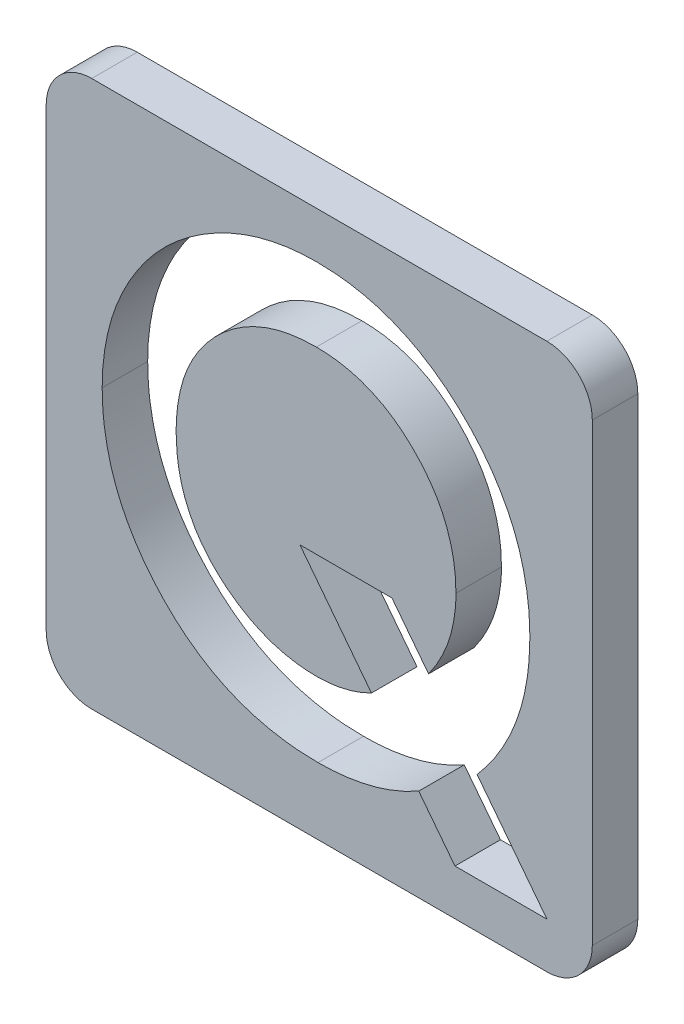
SolidWorks part; units mm, degrees
ref_plane "Front Plane" through (0, 0, 0) normal (0, 0, 1) x (1, 0, 0)
ref_plane "Top Plane" through (0, 0, 0) normal (0, 1, 0) x (1, 0, 0)
ref_plane "Right Plane" through (0, 0, 0) normal (1, 0, 0) x (0, 0, -1)
sketch "Sketch1" plane through (0, 0, 0) normal (0, 0, 1) x (1, 0, 0)
  line L1 (-50, 60) -> (50, 60)
  line L2 (-60, 50) -> (-60, -50)
  line L3 (-50, -60) -> (50, -60)
  line L4 (60, 50) -> (60, -50)
  line L5 (-60, 60) -> (60, -60) construction
  line L6 (-60, -60) -> (60, 60) construction
  arc A0 (-60, -50) -> (-50, -60) centre (-50, -50) ccw
  arc A1 (50, -60) -> (60, -50) centre (50, -50) ccw
  arc A2 (50, 60) -> (60, 50) centre (50, 50) cw
  arc A3 (-50, 60) -> (-60, 50) centre (-50, 50) ccw
  point P0 (0, 0)
  dimension "D3" = 10
  dimension "D1" = 120
  dimension "D2" = 120
extrude "Boss-Extrude1" add sketch "Sketch1" along normal blind 10 contours A3 L2 A0 L3 A1 L4 A2 L1
sketch "Sketch2" plane through (0, 0, 10) normal (0, 0, 1) x (1, 0, 0)
  line L0 (0, 0) -> (0, 40) construction
  line L1 (-50, 50) -> (50, 50) construction
  line L2 (-50, 50) -> (-50, -50) construction
  line L3 (-50, -50) -> (50, -50) construction
  line L4 (50, 50) -> (50, -50) construction
  line L5 (-50, 50) -> (50, -50) construction
  line L6 (-50, -50) -> (50, 50) construction
  line L7 (0, 40) -> (-40, 40) construction
  line L8 (-40, 40) -> (-40, 0) construction
  line L9 (-40, 0) -> (0, 0) construction
  line L11 (0, 20) -> (-20, 20) construction
  line L12 (-20, 40) -> (-20, 20) construction
  circle A0 centre (0, 40) radius 4 construction
  circle A1 centre (0, 20) radius 4 construction
  circle A2 centre (0, 0) radius 4 construction
  circle A3 centre (-20, 20) radius 4 construction
  circle A4 centre (-20, 40) radius 4 construction
  circle A5 centre (-40, 40) radius 4 construction
  circle A6 centre (0, 0) radius 4 construction
  circle A7 centre (20, 0) radius 4 construction
  circle A8 centre (40, 0) radius 4 construction
  circle A9 centre (40, 20) radius 4 construction
  circle A10 centre (40, 40) radius 4 construction
  circle A11 centre (20, 20) radius 4 construction
  circle A12 centre (0, 0) radius 4 construction
  circle A13 centre (0, -20) radius 4 construction
  circle A14 centre (0, -40) radius 4 construction
  circle A15 centre (20, -40) radius 4 construction
  circle A16 centre (40, -40) radius 4 construction
  circle A17 centre (20, -20) radius 4 construction
  circle A18 centre (0, 0) radius 4 construction
  circle A19 centre (-20, 0) radius 4 construction
  circle A20 centre (-40, 0) radius 4 construction
  circle A21 centre (-40, -20) radius 4 construction
  circle A22 centre (-40, -40) radius 4 construction
  circle A23 centre (-20, -20) radius 4 construction
  text T0 "Q" font "Century Gothic" height 90.5
  point P0 (0, 0)
  point P55 (0, 0)
  dimension "D4" = 8
  dimension "D1" = 100
  dimension "D2" = 100
  dimension "D3" = 40
  dimension "D5" = 4
extrude "Cut-Extrude30" cut sketch "Sketch2" against normal blind 10
